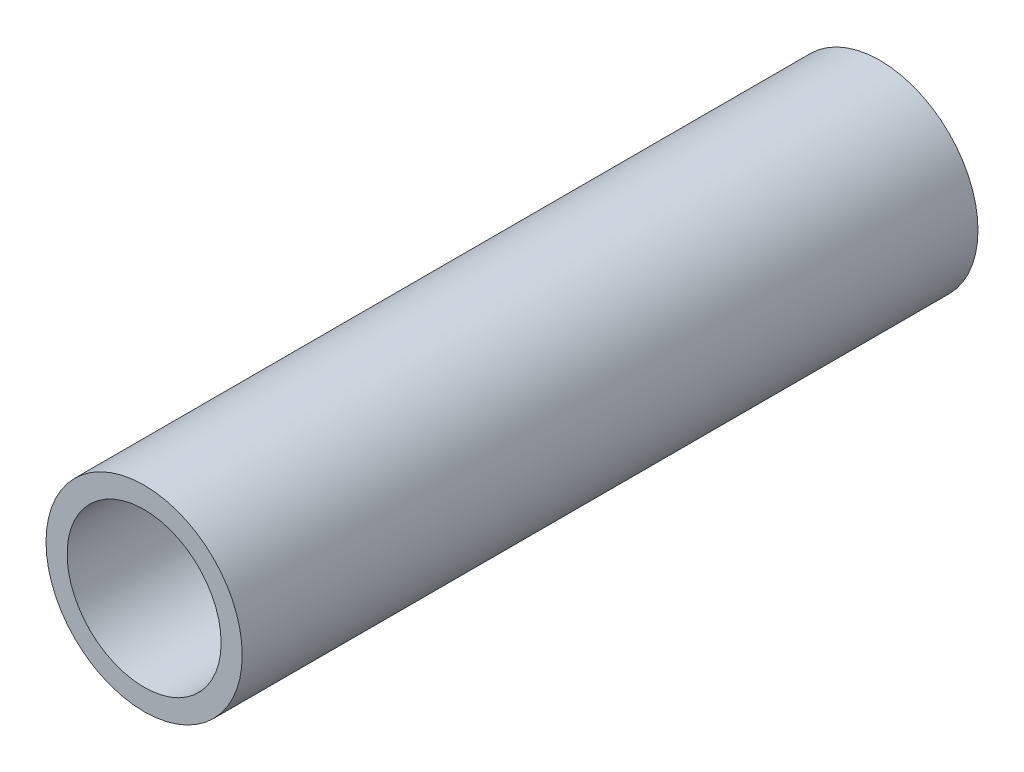
SolidWorks part; units mm, degrees
material "PVC Rigid"
ref_plane "Front Plane" through (0, 0, 0) normal (0, 0, 1) x (1, 0, 0)
ref_plane "Top Plane" through (0, 0, 0) normal (0, 1, 0) x (1, 0, 0)
ref_plane "Right Plane" through (0, 0, 0) normal (1, 0, 0) x (0, 0, -1)
sketch "Sketch1" plane through (0, 0, 0) normal (0, 0, 1) x (1, 0, 0)
  line L0 (10.4648, 0) -> (13.335, 0) construction
  circle A0 centre (0, 0) radius 13.335 construction
  circle A1 centre (0, 0) radius 10.4648 construction
  dimension "ID" = 20.9296
  dimension "OD" = 26.67
  dimension "Wall Thickness" = 2.8702
sketch "Sketch2" plane through (0, 0, 0) normal (1, 0, 0) x (0, 0, -1)
  line L0 (-50, 0) -> (50, 0) construction
  line L1 (-16.6625, 13.335) -> (-16.6625, -13.335) construction
  line L2 (16.6625, 13.335) -> (16.6625, -13.335) construction
  point P4 (0, 0)
  point P8 (-16.6625, 0)
  point P11 (16.6625, 0)
  dimension "Length" = 100
  dimension "D1" = 33.3375
  dimension "D2" = 33.3375
  dimension "D3" = 26.67
sketch "Sketch3" plane through (0, 0, 0) normal (0, 0, 1) x (1, 0, 0)
  circle A0 centre (0, 0) radius 13.335
  circle A1 centre (0, 0) radius 13.335 construction
  circle A2 centre (0, 0) radius 10.4648 construction
  circle A3 centre (0, 0) radius 10.4648
extrude "Boss-Extrude1" add sketch "Sketch3" along normal up to vertex (50 mm away) and the other way up to vertex (50 mm away) up to point (0, 0, 50) other way up to point (0, 0, -50)
ref_plane "Plane1" [suppressed] through (13.335, 0, 0) normal (1, 0, 0) x (0, 0, -1)
sketch "Sketch4" [suppressed] plane through (13.335, 0, 0) normal (1, 0, 0) x (0, 0, -1)
  line L0 (-177.8, 13.335) -> (-177.8, -13.335) construction
  line L1 (-177.8, 0) -> (177.8, 0) construction
  line L2 (177.8, -10.4648) -> (177.8, 10.4648) construction
  point P0 (-104.775, 0)
  point P1 (-41.275, 0)
  point P3 (41.275, 0)
  point P5 (104.775, 0)
  point P6 (0, 0)
  dimension "D2" = 63.5
  dimension "D4" = 63.5
  dimension "D1" = 82.55
  dimension "D3" = 41.275
hole_wizard "1/8 (0.125) Diameter Hole1" [suppressed] positions "Sketch5" profile "Sketch6" hole size "1/8" standard "ANSI Inch"
sketch "Sketch5" [suppressed] plane through (13.335, 0, 0) normal (1, 0, 0) x (0, 0, -1)
  point P0 (-104.775, 0)
  point P3 (-41.275, 0)
  point P9 (41.275, 0)
  point P12 (104.775, 0)
sketch "Sketch6" plane through (13.335, 0, 104.775) normal (0, 1, 0) x (0, 0, -1)
  line L0 (0, 0) -> (0, 2.8702)
  line L1 (0, 2.8702) -> (1.5875, 2.8702)
  line L2 (1.5875, 2.8702) -> (1.5875, 0)
  line L5 (1.5875, 0) -> (0, 0)
  line L11 (0, -6.35) -> (0, 107.95) construction
  dimension "Thru Hole Dia." = 3.175
  dimension "Thru Hole Depth" = 2.8702
equation "\"D1@Sketch2\"=\"OD@Sketch1\" * 1.25"
equation "\"D2@Sketch2\"=\"D1@Sketch2\""
equation "\"D3@Sketch2\"= \"OD@Sketch1\""
equation "\"D3@Sketch4\"=\"D1@Sketch4\"/2"
equation "\"Length@Sketch2\"=100mm"
